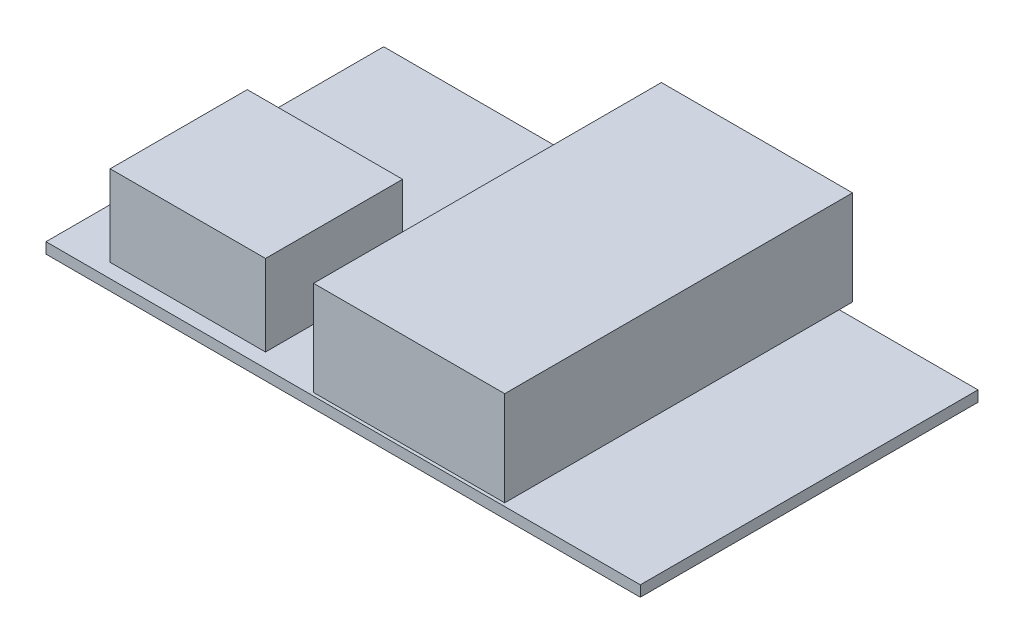
SolidWorks part; units mm, degrees
ref_plane "Front Plane" through (0, 0, 0) normal (0, 0, 1) x (1, 0, 0)
ref_plane "Top Plane" through (0, 0, 0) normal (0, 1, 0) x (1, 0, 0)
ref_plane "Right Plane" through (0, 0, 0) normal (1, 0, 0) x (0, 0, -1)
sketch "Croquis_pcb" plane through (0, 0, 0) normal (0, 1, 0) x (1, 0, 0)
  line L1 (-44, -25) -> (44, -25)
  line L2 (-44, -25) -> (-44, 25)
  line L3 (-44, 25) -> (44, 25)
  line L4 (44, -25) -> (44, 25)
  line L5 (-44, -25) -> (44, 25) construction
  line L6 (-44, 25) -> (44, -25) construction
  point P0 (0, 0)
  dimension "D1" = 88
  dimension "D2" = 50
extrude "PCB" add sketch "Croquis_pcb" along normal blind 1.6
ref_plane "Plano_Top Plane_+1_6" through (0, 1.6, 0) normal (0, 1, 0) x (1, 0, 0)
sketch "Croquis_esp32" plane through (0, 1.6, 0) normal (0, 1, 0) x (1, 0, 0)
  line L1 (-4.85, -24.53) -> (23.45, -24.53)
  line L2 (-4.85, -24.53) -> (-4.85, 26.97)
  line L3 (-4.85, 26.97) -> (23.45, 26.97)
  line L4 (23.45, -24.53) -> (23.45, 26.97)
  line L5 (-4.85, -24.53) -> (23.45, 26.97) construction
  line L6 (-4.85, 26.97) -> (23.45, -24.53) construction
  dimension "D1" = 28.3
  dimension "D2" = 51.5
extrude "ESP32" add sketch "Croquis_esp32" along normal blind 14
sketch "Croquis_ina219" plane through (0, 1.6, 0) normal (0, 1, 0) x (1, 0, 0)
  line L1 (-36.6, -22.9) -> (-13.6, -22.9)
  line L2 (-36.6, -22.9) -> (-36.6, -2.6)
  line L3 (-36.6, -2.6) -> (-13.6, -2.6)
  line L4 (-13.6, -22.9) -> (-13.6, -2.6)
  line L5 (-36.6, -22.9) -> (-13.6, -2.6) construction
  line L6 (-36.6, -2.6) -> (-13.6, -22.9) construction
  dimension "D1" = 23
  dimension "D2" = 20.3
extrude "INA219" add sketch "Croquis_ina219" along normal blind 12
